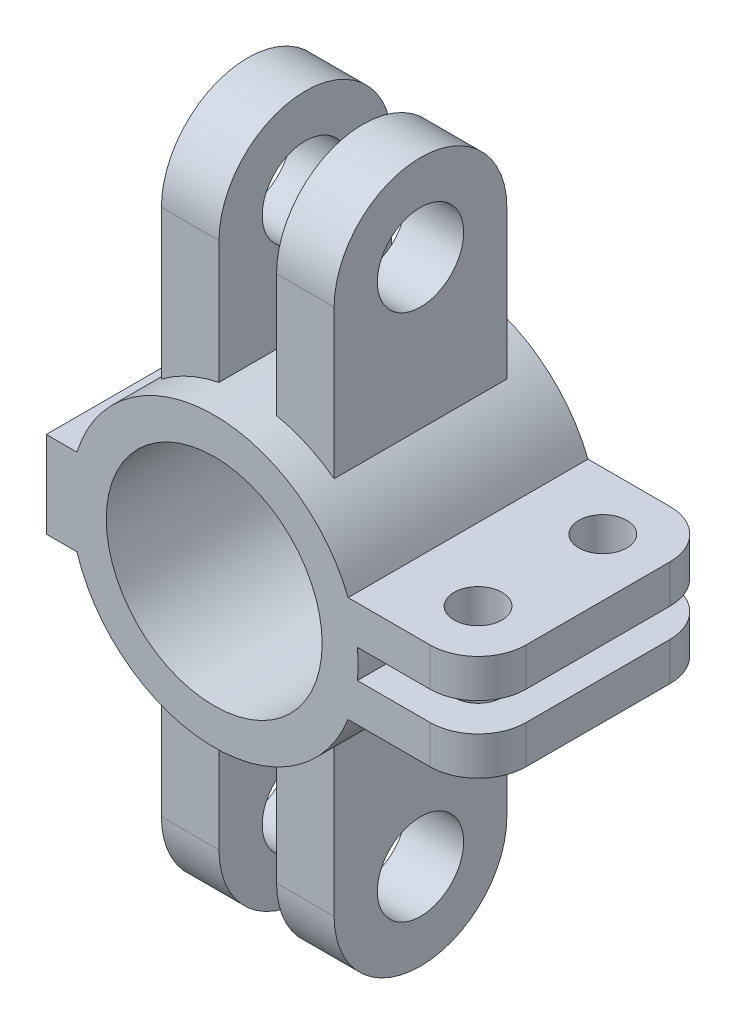
SolidWorks part; units mm, degrees
ref_plane "Front Plane" through (0, 0, 0) normal (0, 0, 1) x (1, 0, 0)
ref_plane "Top Plane" through (0, 0, 0) normal (0, 1, 0) x (1, 0, 0)
ref_plane "Right Plane" through (0, 0, 0) normal (1, 0, 0) x (0, 0, -1)
sketch "Sketch1" plane through (0, 0, 0) normal (1, 0, 0) x (0, 0, -1)
  line L0 (0, 55) -> (0, -55) construction
  line L1 (18, 55) -> (18, -55)
  line L2 (-18, 55) -> (-18, -55)
  arc A0 (18, 55) -> (-18, 55) centre (0, 55) ccw
  arc A1 (-18, -55) -> (18, -55) centre (0, -55) ccw
  point P3 (0, 0)
  point P8 (0, 15.9532)
  dimension "D1" = 18
  dimension "D2" = 110
extrude "Boss-Extrude1" add sketch "Sketch1" along normal blind 12 from offset 6
sketch "Sketch2" plane through (0, 0, 0) normal (1, 0, 0) x (0, 0, -1)
  line L0 (18, -55) -> (18, 55) construction
  line L1 (-18, 55) -> (-18, -55) construction
  line L2 (18, -55) -> (18, 55)
  line L3 (-18, 55) -> (-18, -55)
  arc A0 (-18, -55) -> (18, -55) centre (0, -55) ccw construction
  arc A1 (18, 55) -> (-18, 55) centre (0, 55) ccw construction
  arc A2 (-18, -55) -> (18, -55) centre (0, -55) ccw
  arc A3 (18, 55) -> (-18, 55) centre (0, 55) ccw
extrude "Boss-Extrude2" add sketch "Sketch2" against normal blind 12 from offset 6 separate body offset against normal yes
sketch "Sketch3" plane through (0, 0, 0) normal (0, 0, 1) x (1, 0, 0)
  line L0 (0, 0) -> (99.3521, 0) construction
  line L1 (-35, 9) -> (-28.6182, 9)
  line L2 (-35, 9) -> (-35, -9)
  line L3 (-35, -9) -> (-28.6182, -9)
  line L5 (-35, 9) -> (-30, 0) construction
  line L6 (-35, -9) -> (-30, 0) construction
  line L8 (29.8496, 3) -> (55, 3)
  line L10 (27.9106, 11) -> (55, 11)
  line L11 (55, 3) -> (55, 11)
  line L12 (29.8496, -3) -> (55, -3)
  line L14 (27.9106, -11) -> (55, -11)
  line L15 (55, -3) -> (55, -11)
  arc A0 (27.9106, 11) -> (-28.6182, 9) centre (0, 0) ccw
  circle A1 centre (0, 0) radius 22.5
  arc A2 (29.8496, -3) -> (29.8496, 3) centre (0, 0) ccw
  arc A3 (-28.6182, -9) -> (27.9106, -11) centre (0, 0) ccw
  point P4 (-30, 0)
  dimension "D1" = 60
  dimension "D2" = 45
  dimension "D3" = 18
  dimension "D4" = 6
  dimension "D5" = 22
  dimension "D6" = 90
  dimension "D7" = 35
extrude "Boss-Extrude3" add sketch "Sketch3" along normal mid plane 50
hole_wizard "Hole1" positions "Sketch4" profile "Sketch5" legacy end condition through all
sketch "Sketch4" plane through (18, 0, 0) normal (1, 0, 0) x (0, 0, -1)
  point P0 (0, 55)
sketch "Sketch5" plane through (18, 55, 0) normal (0, 1, 0) x (0, 0, -1)
  line L0 (0, 0) -> (0, 53)
  line L1 (0, 53) -> (9, 53)
  line L2 (9, 53) -> (9, 0)
  line L3 (9, 0) -> (0, 0)
  line L4 (0, 110) -> (0, -10) construction
  dimension "Diameter" = 18
  dimension "Depth" = 53
hole_wizard "Hole2" positions "Sketch6" profile "Sketch7" legacy end condition through all
sketch "Sketch6" plane through (18, 0, 0) normal (1, 0, 0) x (0, 0, -1)
  point P0 (0, -55)
sketch "Sketch7" plane through (18, -55, 0) normal (0, 1, 0) x (0, 0, -1)
  line L0 (0, 0) -> (0, 53)
  line L1 (0, 53) -> (9, 53)
  line L2 (9, 53) -> (9, 0)
  line L3 (9, 0) -> (0, 0)
  line L4 (0, 110) -> (0, -10) construction
  dimension "Diameter" = 18
  dimension "Depth" = 53
hole_wizard "Hole3" positions "Sketch8" profile "Sketch9" legacy end condition through all
sketch "Sketch8" plane through (0, 11, 0) normal (0, 1, 0) x (1, 0, 0)
  line L0 (55, -25) -> (55, 25) construction
  line L1 (55, -25) -> (27.9106, -25) construction
  point P0 (43, -13)
  dimension "D1" = 12
  dimension "D2" = 12
sketch "Sketch9" plane through (43, 11, 13) normal (1, 0, 0) x (0, 0, 1)
  line L0 (0, 0) -> (0, 84)
  line L1 (0, 84) -> (5, 84)
  line L2 (5, 84) -> (5, 0)
  line L3 (5, 0) -> (0, 0)
  line L4 (0, 110) -> (0, -10) construction
  dimension "Diameter" = 10
  dimension "Depth" = 84
mirror "Mirror2" about plane through (0, 0, 0) normal (0, 0, 1) of "Hole3"
fillet "Fillet1" radius 10 4 edges at (55, 7, -25) (55, -7, -25) (55, -7, 25) (55, 7, 25)
sketch "Sketch11" plane through (0, 0, 0) normal (0, 0, 1) x (1, 0, 0)
  circle A0 centre (0, 0) radius 22.5
  circle A1 centre (0, 0) radius 22.5 construction
extrude "Cut-Extrude1" cut sketch "Sketch11" against normal through all both and the other way through all
